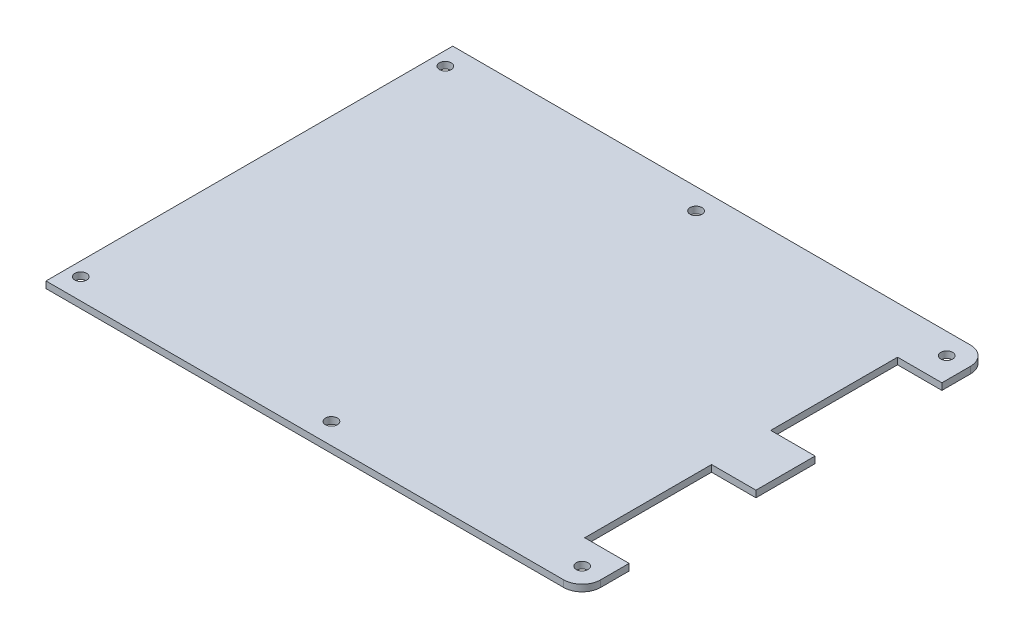
SolidWorks part; units mm, degrees
ref_plane "Front Plane" through (0, 0, 0) normal (0, 0, 1) x (1, 0, 0)
ref_plane "Top Plane" through (0, 0, 0) normal (0, 1, 0) x (1, 0, 0)
ref_plane "Right Plane" through (0, 0, 0) normal (1, 0, 0) x (0, 0, -1)
sketch "Sketch2" plane through (0, 0, 0) normal (0, 1, 0) x (1, 0, 0)
  line L0 (60.5, 8) -> (60.5, -8) construction
  line L1 (-72.5, -55) -> (72.5, -55)
  line L2 (-72.5, -55) -> (-72.5, 55)
  line L3 (-72.5, 55) -> (72.5, 55)
  line L4 (72.5, -55) -> (72.5, -42.3)
  line L5 (-72.5, -55) -> (72.5, 55) construction
  line L6 (-72.5, 55) -> (72.5, -55) construction
  line L7 (72.5, 42.3) -> (60.5, 42.3)
  line L9 (72.5, 8) -> (60.5, 8)
  line L10 (60.5, 42.3) -> (60.5, 8)
  line L11 (72.5, -42.3) -> (60.5, -42.3)
  line L13 (72.5, -8) -> (60.5, -8)
  line L14 (60.5, -42.3) -> (60.5, -8)
  line L15 (72.5, 42.3) -> (72.5, 55)
  line L16 (72.5, -8) -> (72.5, 8)
  point P0 (0, 0)
  point P14 (60.5, 0)
  dimension "D1" = 145
  dimension "D2" = 110
  dimension "D3" = 34.3
  dimension "D4" = 12
  dimension "D5" = 16
extrude "Boss-Extrude2" add sketch "Sketch2" along normal blind 1.8
fillet "Fillet1" radius 5 2 edges at (72.5, 0.9, -55) (72.5, 0.9, 55)
sketch "Sketch3" plane through (0, 1.8, 0) normal (0, 1, 0) x (1, 0, 0)
  line L3 (-68.8, 49.3) -> (-68.8, -49.3) construction
  circle A0 centre (-68.8, 49.3) radius 1.6
  circle A1 centre (-1, 49.3) radius 1.6
  circle A2 centre (-1, -49.3) radius 1.6
  circle A3 centre (-68.8, -49.3) radius 1.6
  circle A4 centre (66.8, 49.3) radius 1.6
  circle A5 centre (66.8, -49.3) radius 1.6
  point P3 (-68.8, 0)
  point P4 (0, 0)
  point P5 (-1.9916, 49.3)
  dimension "D1" = 3.2
  dimension "D4" = 135.6
  dimension "D5" = 98.6
  dimension "D6" = 1
  dimension "D2" = 3
  dimension "D3" = 2
extrude "Cut-Extrude1" cut sketch "Sketch3" against normal up to next
